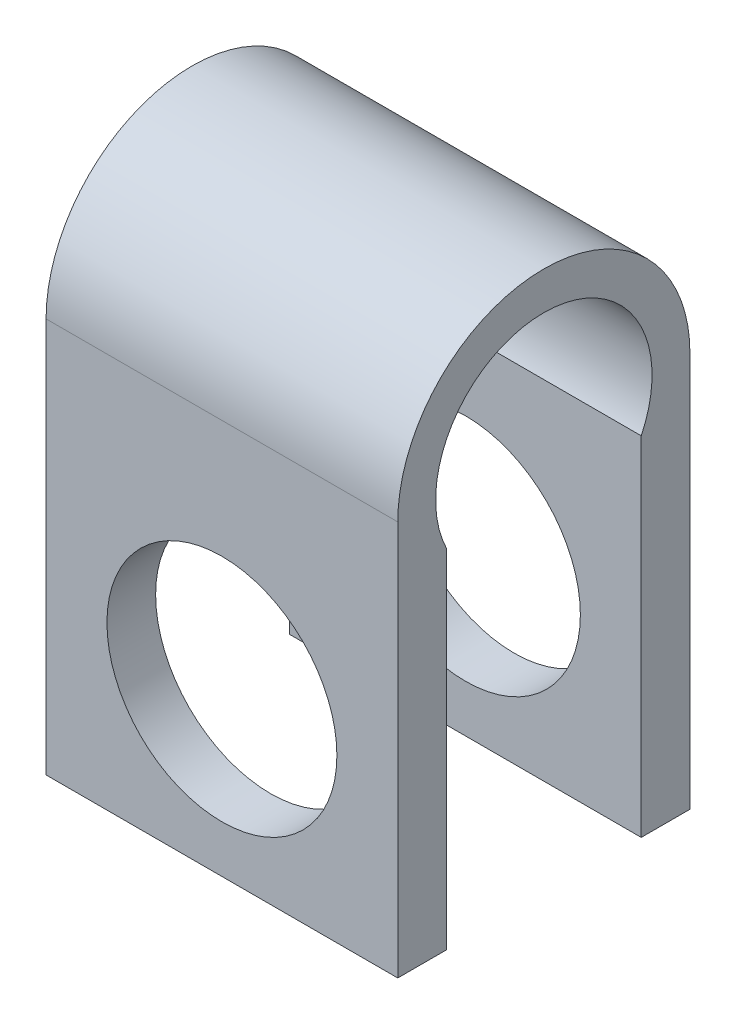
SolidWorks part; units mm, degrees
ref_plane "Front Plane" through (0, 0, 0) normal (0, 0, 1) x (1, 0, 0)
ref_plane "Top Plane" through (0, 0, 0) normal (0, 1, 0) x (1, 0, 0)
ref_plane "Right Plane" through (0, 0, 0) normal (1, 0, 0) x (0, 0, -1)
sketch "Sketch1" plane through (0, 0, 0) normal (1, 0, 0) x (0, 0, -1)
  line L0 (5.4, 0) -> (5.4, -14.6)
  line L1 (5.4, -14.6) -> (3.6, -14.6)
  line L2 (3.6, -14.6) -> (3.6, -1.7436)
  line L3 (0, -5.4) -> (0, 5.4) construction
  line L4 (-3.6, -14.6) -> (-3.6, -1.7436)
  line L5 (-5.4, -14.6) -> (-3.6, -14.6)
  line L6 (-5.4, 0) -> (-5.4, -14.6)
  arc A0 (5.4, 0) -> (-5.4, 0) centre (0, 0) ccw
  arc A1 (3.6, -1.7436) -> (-3.6, -1.7436) centre (0, 0) ccw
  dimension "D1" = 10.8
  dimension "D2" = 8
  dimension "D3" = 90
  dimension "D4" = 1.8
extrude "Boss-Extrude1" add sketch "Sketch1" along normal blind 13
sketch "Sketch2" plane through (0, 0, 5.4) normal (0, 0, 1) x (1, 0, 0)
  line L0 (6.5, -14.6) -> (6.5, 0) construction
  line L1 (13, -14.6) -> (0, -14.6) construction
  line L2 (13, 0) -> (0, 0) construction
  circle A0 centre (6.5, -8.6) radius 4.25
  dimension "D1" = 8.5
  dimension "D2" = 6
extrude "Cut-Extrude1" cut sketch "Sketch2" against normal through all
